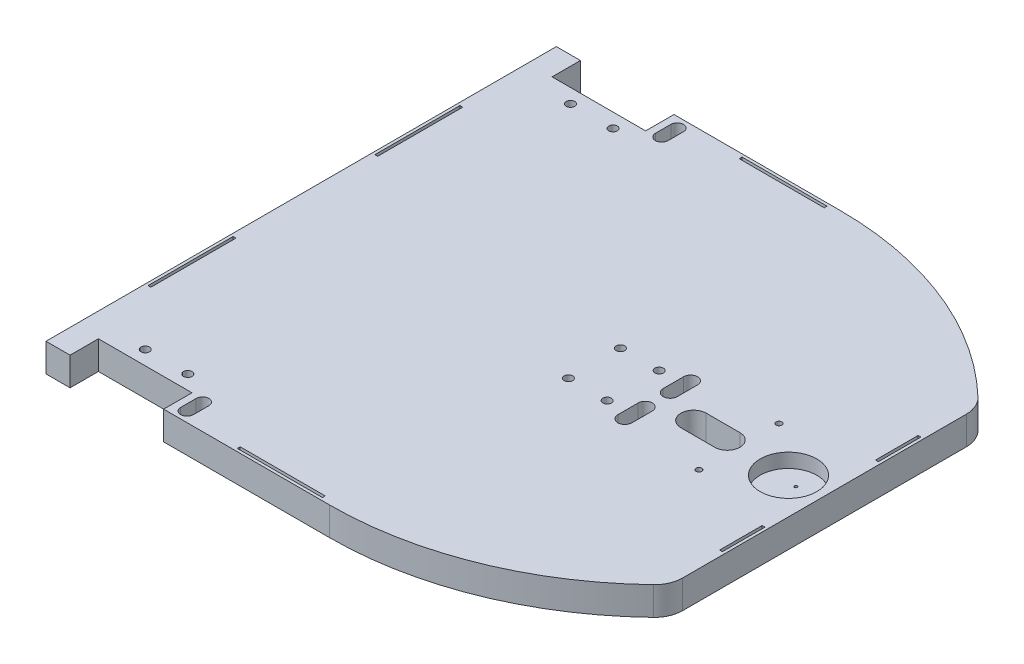
SolidWorks part; units mm, degrees
ref_plane "Front Plane" through (0, 0, 0) normal (0, 0, 1) x (1, 0, 0)
ref_plane "Top Plane" through (0, 0, 0) normal (0, 1, 0) x (1, 0, 0)
ref_plane "Right Plane" through (0, 0, 0) normal (1, 0, 0) x (0, 0, -1)
sketch "Sketch1" plane through (0, 0, 0) normal (0, 1, 0) x (1, 0, 0)
  line L0 (-89.3891, 0) -> (95.1826, 0) construction
  line L1 (-89.3891, -90) -> (-89.3891, 90)
  line L2 (-89.3891, 90) -> (10.6109, 90)
  line L3 (95.1826, 50) -> (95.1826, -50)
  line L4 (-89.3891, -90) -> (10.6109, -90)
  arc A0 (10.6109, 90) -> (92.1078, 57.214) centre (10.6109, -27.6825) cw
  arc A1 (92.1078, 57.214) -> (95.1826, 50) centre (85.1826, 50) cw
  arc A2 (92.1078, -57.214) -> (95.1826, -50) centre (85.1826, -50) ccw
  arc A3 (10.6109, -90) -> (92.1078, -57.214) centre (10.6109, 27.6825) ccw
  dimension "D1" = 10
  dimension "D2" = 180
  dimension "D3" = 100
  dimension "D4" = 100
extrude "Boss-Extrude1" add sketch "Sketch1" along normal blind 10
sketch "Sketch2" plane through (0, 10, 0) normal (0, 1, 0) x (1, 0, 0)
  line L0 (-89.3891, 0) -> (95.1826, 0) construction
  line L1 (-89.3891, 90) -> (-89.3891, -90) construction
  line L2 (95.1826, -50) -> (95.1826, 50) construction
  line L4 (36.3663, -11.5949) -> (36.3663, -4.4051) construction
  line L7 (-43.2044, 86.4271) -> (-43.2044, 80.9729) construction
  line L8 (-40.9689, 86.4271) -> (-40.9689, 80.9729)
  line L9 (-45.4398, 86.4271) -> (-45.4398, 80.9729)
  line L10 (36.3663, 11.5949) -> (36.3663, 4.4051) construction
  line L11 (38.8455, 11.5949) -> (38.8455, 4.4051)
  line L12 (33.887, 11.5949) -> (33.887, 4.4051)
  line L14 (10.6109, 90) -> (-89.3891, 90) construction
  line L15 (-80.901, 90) -> (-47.901, 90)
  line L16 (-80.901, 90) -> (-80.901, 80)
  line L17 (-80.901, 80) -> (-47.901, 80)
  line L18 (-47.901, 90) -> (-47.901, 80)
  line L19 (38.8455, -11.5949) -> (38.8455, -4.4051)
  line L20 (33.887, -11.5949) -> (33.887, -4.4051)
  line L21 (-43.2044, -86.4271) -> (-43.2044, -80.9729) construction
  line L22 (-40.9689, -86.4271) -> (-40.9689, -80.9729)
  line L23 (-45.4398, -86.4271) -> (-45.4398, -80.9729)
  line L24 (-80.901, -80) -> (-47.901, -80)
  line L25 (-47.901, -90) -> (-47.901, -80)
  line L26 (-80.901, -90) -> (-47.901, -90)
  line L27 (-80.901, -90) -> (-80.901, -80)
  circle A0 centre (65, 14.1316) radius 1
  circle A1 centre (27.689, 9.1731) radius 1.5
  circle A2 centre (14.0532, 9.1731) radius 1.5
  arc A3 (-40.9689, 86.4271) -> (-45.4398, 86.4271) centre (-43.2044, 86.4271) ccw
  arc A4 (-45.4398, 80.9729) -> (-40.9689, 80.9729) centre (-43.2044, 80.9729) ccw
  arc A5 (38.8455, 11.5949) -> (33.887, 11.5949) centre (36.3663, 11.5949) ccw
  arc A6 (33.887, 4.4051) -> (38.8455, 4.4051) centre (36.3663, 4.4051) ccw
  circle A7 centre (14.0532, -9.1731) radius 1.5
  circle A8 centre (27.689, -9.1731) radius 1.5
  circle A9 centre (65, -14.1316) radius 1
  arc A10 (38.8455, -11.5949) -> (33.887, -11.5949) centre (36.3663, -11.5949) cw
  arc A11 (33.887, -4.4051) -> (38.8455, -4.4051) centre (36.3663, -4.4051) cw
  arc A12 (-40.9689, -86.4271) -> (-45.4398, -86.4271) centre (-43.2044, -86.4271) cw
  arc A13 (-45.4398, -80.9729) -> (-40.9689, -80.9729) centre (-43.2044, -80.9729) cw
  point P20 (-43.2044, 83.7)
  point P25 (36.3663, 8)
  point P41 (36.3663, -8)
  point P48 (-43.2044, -83.7)
  dimension "D1" = 10
  dimension "D2" = 33
extrude "Cut-Extrude2" cut sketch "Sketch2" against normal mid plane 30 contours L17 L18 L15 L16 | L24 L25 L26 L27 | L19 A11 L20 A10 | L11 A6 L12 A5 | A1 | A2 | A7 | A8 | A9 | A0 | L8 A4 L9 A3 | L22 A13 L23 A12
sketch "Sketch3" plane through (0, 10, 0) normal (0, 1, 0) x (1, 0, 0)
  line L0 (12.3178, 0) -> (112.2305, 0) construction
  circle A0 centre (82.4798, 0) radius 10
extrude "Cut-Extrude3" cut sketch "Sketch3" against normal mid plane 10
sketch "Sketch4" plane through (0, 10, 0) normal (0, 1, 0) x (1, 0, 0)
  line L0 (49.0103, 0) -> (60.9106, 0) construction
  line L1 (49.0103, 4.4626) -> (60.9106, 4.4626)
  line L2 (49.0103, -4.4626) -> (60.9106, -4.4626)
  arc A0 (49.0103, 4.4626) -> (49.0103, -4.4626) centre (49.0103, 0) ccw
  arc A1 (60.9106, -4.4626) -> (60.9106, 4.4626) centre (60.9106, 0) ccw
  point P3 (54.9604, 0)
extrude "Cut-Extrude4" cut sketch "Sketch4" against normal mid plane 30
sketch "Sketch5" plane through (0, 10, 0) normal (0, 1, 0) x (1, 0, 0)
  line L0 (10.6109, 90) -> (-47.901, 90) construction
  line L1 (-22.901, 89) -> (7.099, 89)
  line L2 (-22.901, 89) -> (-22.901, 88)
  line L3 (-22.901, 88) -> (7.099, 88)
  line L4 (7.099, 89) -> (7.099, 88)
  line L5 (-88.3891, 55) -> (-87.3891, 55)
  line L6 (-88.3891, 55) -> (-88.3891, 25)
  line L7 (-88.3891, 25) -> (-87.3891, 25)
  line L8 (-87.3891, 55) -> (-87.3891, 25)
  line L9 (93.1826, 35) -> (94.1826, 35)
  line L10 (93.1826, 35) -> (93.1826, 20)
  line L11 (93.1826, 20) -> (94.1826, 20)
  line L12 (94.1826, 35) -> (94.1826, 20)
  line L13 (95.1826, -50) -> (95.1826, 50) construction
  line L14 (-89.3891, 90) -> (-89.3891, -90) construction
  line L15 (-89.3891, 0) -> (94.1826, 0) construction
  line L16 (93.1826, -20) -> (94.1826, -20)
  line L17 (94.1826, -35) -> (94.1826, -20)
  line L18 (93.1826, -35) -> (94.1826, -35)
  line L19 (93.1826, -35) -> (93.1826, -20)
  line L20 (-22.901, -88) -> (7.099, -88)
  line L21 (7.099, -89) -> (7.099, -88)
  line L22 (-22.901, -89) -> (7.099, -89)
  line L23 (-22.901, -89) -> (-22.901, -88)
  line L24 (-88.3891, -25) -> (-87.3891, -25)
  line L25 (-87.3891, -55) -> (-87.3891, -25)
  line L26 (-88.3891, -55) -> (-87.3891, -55)
  line L27 (-88.3891, -55) -> (-88.3891, -25)
  line L28 (-47.901, 80) -> (-47.901, 90) construction
  dimension "D1" = 1
  dimension "D2" = 30
  dimension "D3" = 1
  dimension "D4" = 30
  dimension "D5" = 1
  dimension "D6" = 15
  dimension "D7" = 1
  dimension "D8" = 1
  dimension "D9" = 1
  dimension "D10" = 25
  dimension "D11" = 20
  dimension "D12" = 20
  dimension "D13" = 25
extrude "Cut-Extrude6" cut sketch "Sketch5" against normal mid plane 30 contours L6 L7 L8 L5 | L1 L4 L3 L2 | L10 L11 L12 L9 | L17 L16 L19 L18 | L20 L21 L22 L23 | L25 L24 L27 L26
sketch "Sketch6" plane through (0, 5, 0) normal (0, 1, 0) x (1, 0, 0)
  circle A0 centre (82.2441, 2.8356) radius 0.5
  circle A1 centre (82.2441, -5.1644) radius 0.5
  dimension "D1" = 8
extrude "Cut-Extrude7" cut sketch "Sketch6" against normal mid plane 30 contours A1 | A0
sketch "Sketch7" plane through (0, 10, 0) normal (0, 1, 0) x (1, 0, 0)
  line L0 (-89.3891, 90) -> (-89.3891, -90) construction
  line L1 (-47.901, 80) -> (-80.901, 80) construction
  line L2 (-89.3891, 0) -> (95.1826, 0) construction
  line L3 (95.1826, -50) -> (95.1826, 50) construction
  circle A0 centre (-69.3891, 75) radius 1.5
  circle A1 centre (-54.3891, 75) radius 1.5
  circle A2 centre (-69.3891, -75) radius 1.5
  circle A3 centre (-54.3891, -75) radius 1.5
  point P12 (-54.3891, -75)
  point P13 (-69.3891, -75)
  dimension "D1" = 15
  dimension "D2" = 20
  dimension "D3" = 5
extrude "Cut-Extrude8" cut sketch "Sketch7" against normal through all
